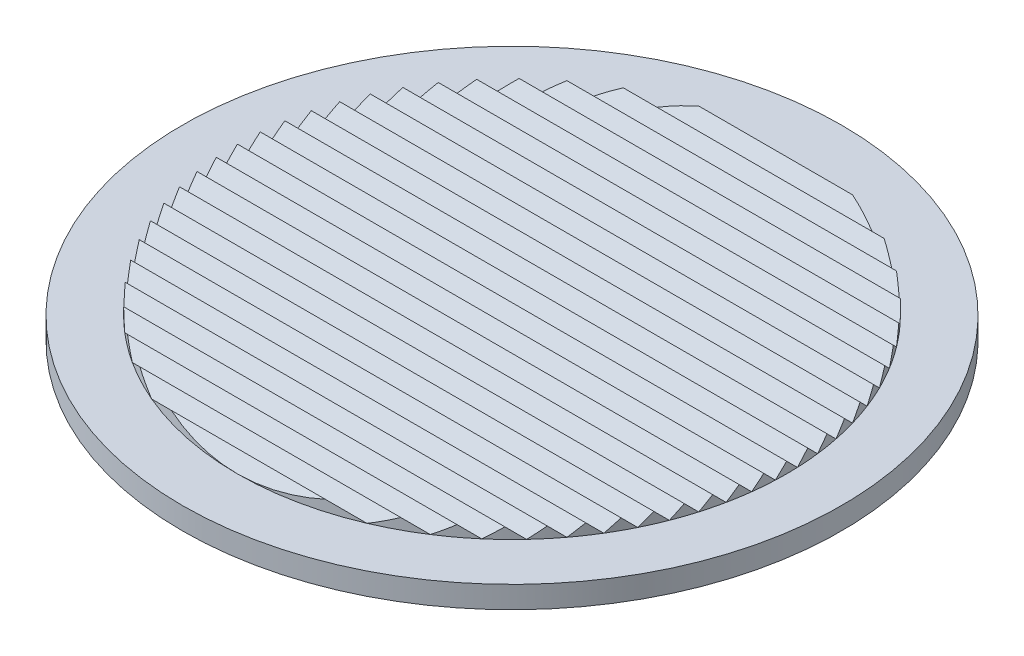
SolidWorks part; units mm, degrees
ref_plane "Front Plane" through (0, 0, 0) normal (0, 0, 1) x (1, 0, 0)
ref_plane "Top Plane" through (0, 0, 0) normal (0, 1, 0) x (1, 0, 0)
ref_plane "Right Plane" through (0, 0, 0) normal (1, 0, 0) x (0, 0, -1)
sketch "Sketch1" plane through (0, 0, 0) normal (0, 1, 0) x (1, 0, 0)
  line L1 (-30, 30) -> (30, 30)
  line L2 (-30, 30) -> (-30, -30)
  line L3 (-30, -30) -> (30, -30)
  line L4 (30, 30) -> (30, -30)
  circle A0 centre (0, 0) radius 30 construction
  dimension "D1" = 60
extrude "Boss-Extrude1" add sketch "Sketch1" along normal blind 2
sketch "Sketch2" plane through (0, 2, 0) normal (0, 1, 0) x (1, 0, 0)
  line L0 (-30, 0) -> (30, 0) construction
  line L1 (-30, 30) -> (-30, -30) construction
  line L2 (30, -30) -> (30, 30) construction
  line L3 (-30, -1) -> (30, -1)
  line L4 (-30, 1) -> (30, 1)
  line L5 (-30, -1) -> (-30, 1)
  line L6 (30, -1) -> (30, 1)
  dimension "D1" = 1
  dimension "D2" = 1
extrude "Boss-Extrude2" add sketch "Sketch2" along normal blind 1 draft 45
pattern_linear "LPattern1" count 15 spacing 2 along (0, 0, 1) count 15 spacing 2 along (0, 0, -1) of "Boss-Extrude2"
sketch "Sketch3" plane through (0, 0, 0) normal (0, -1, 0) x (1, 0, 0)
  line L0 (30, -30) -> (-30, -30) construction
  circle A0 centre (0, 0) radius 30
extrude "Cut-Extrude1" cut sketch "Sketch3" against normal through all flip side to cut
ref_plane "Plane2" through (0, 2, 0) normal (0, -1, 0) x (-1, 0, 0)
sketch "Sketch5" plane through (0, 2, 0) normal (0, -1, 0) x (-1, 0, 0)
  circle A0 centre (0, 0) radius 25
  dimension "D1" = 50
extrude "Cut-Extrude3" cut sketch "Sketch5" against normal blind 1 flip side to cut
sketch "Sketch6" plane through (0, 2, 0) normal (0, -1, 0) x (-1, 0, 0)
  line L0 (0, 0) -> (0, 33.0133) construction
  line L1 (0, 0) -> (-19.7605, 28.2209) construction
  circle A0 centre (0, 0) radius 30 construction
  point P3 (-8.6036, 12.2873)
  dimension "D1" = 35
  dimension "D2" = 15
